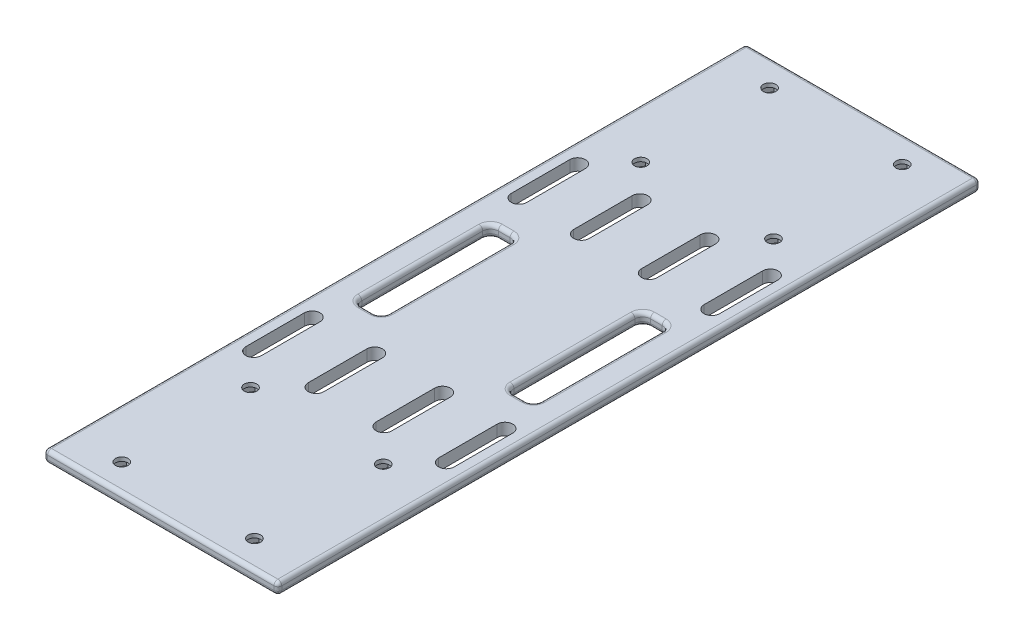
SolidWorks part; units mm, degrees
ref_plane "Front" through (0, 0, 0) normal (0, 0, 1) x (1, 0, 0)
ref_plane "Top" through (0, 0, 0) normal (0, 1, 0) x (1, 0, 0)
ref_plane "Right" through (0, 0, 0) normal (1, 0, 0) x (0, 0, -1)
sketch "Sketch1" plane through (0, 0, 0) normal (0, 1, 0) x (1, 0, 0)
  line L0 (0, 75.349) -> (0, -71.6607) construction
  line L1 (-30, 90) -> (30, 90)
  line L2 (-30, 90) -> (-30, -90)
  line L3 (-30, -90) -> (30, -90)
  line L4 (30, 90) -> (30, -90)
  line L5 (-30, 90) -> (30, -90) construction
  line L6 (-30, -90) -> (30, 90) construction
  line L7 (-47.0197, 0) -> (48.1207, 0) construction
  circle A0 centre (-17, 83) radius 1.6
  circle A1 centre (-17, 50) radius 1.6
  circle A2 centre (17, 50) radius 1.6
  circle A3 centre (17, 83) radius 1.6
  circle A4 centre (-17, -50) radius 1.6
  circle A5 centre (17, -50) radius 1.6
  circle A6 centre (17, -83) radius 1.6
  circle A7 centre (-17, -83) radius 1.6
  point P0 (0, 0)
  dimension "D3" = 3.2
  dimension "D1" = 60
  dimension "D2" = 180
  dimension "D4" = 7
  dimension "D5" = 13
  dimension "D6" = 33
extrude "Boss-Extrude1" add sketch "Sketch1" along normal blind 3
sketch "Sketch2" plane through (0, 3, 0) normal (0, 1, 0) x (1, 0, 0)
  line L8 (0, -69.3107) -> (0, 75.504) construction
  line L15 (30, -90) -> (30, 90) construction
  line L16 (21, -17.5) -> (18, -17.5)
  line L17 (23, -15.5) -> (23, 15.5)
  line L18 (21, 17.5) -> (18, 17.5)
  line L19 (16, -15.5) -> (16, 15.5)
  line L20 (23, -17.5) -> (16, 17.5) construction
  line L21 (23, 17.5) -> (16, -17.5) construction
  line L22 (-23, 17.5) -> (-16, -17.5) construction
  line L23 (-23, -17.5) -> (-16, 17.5) construction
  line L24 (-16, -15.5) -> (-16, 15.5)
  line L25 (-21, 17.5) -> (-18, 17.5)
  line L26 (-23, -15.5) -> (-23, 15.5)
  line L27 (-21, -17.5) -> (-18, -17.5)
  arc A0 (18, -17.5) -> (16, -15.5) centre (18, -15.5) cw
  arc A1 (21, -17.5) -> (23, -15.5) centre (21, -15.5) ccw
  arc A2 (18, 17.5) -> (16, 15.5) centre (18, 15.5) ccw
  arc A3 (23, 15.5) -> (21, 17.5) centre (21, 15.5) ccw
  arc A4 (-23, 15.5) -> (-21, 17.5) centre (-21, 15.5) cw
  arc A5 (-18, 17.5) -> (-16, 15.5) centre (-18, 15.5) cw
  arc A6 (-21, -17.5) -> (-23, -15.5) centre (-21, -15.5) cw
  arc A7 (-18, -17.5) -> (-16, -15.5) centre (-18, -15.5) ccw
  point P0 (19.5, 0)
  point P7 (16, 0)
  point P39 (-19.5, 0)
  dimension "D1" = 7
  dimension "D4" = 2
  dimension "D2" = 35
  dimension "D3" = 7
extrude "Cut-Extrude1" cut sketch "Sketch2" against normal blind 72
fillet "Fillet2" radius 1 2 edges at (-30, 3, 0) (30, 0, 0)
sketch "Sketch3" plane through (0, 0, 0) normal (0, -1, 0) x (-1, 0, 0)
  circle A0 centre (0, 30.4779) radius 1
extrude "Cut-Extrude2" cut sketch "Sketch3" against normal blind 1
sketch "Sketch4" plane through (0, 0, 0) normal (0, -1, 0) x (-1, 0, 0)
  line L1 (-13.8246, 83) -> (-15.4123, 85.75)
  line L2 (-15.4123, 85.75) -> (-18.5877, 85.75)
  line L3 (-18.5877, 85.75) -> (-20.1754, 83)
  line L4 (-20.1754, 83) -> (-18.5877, 80.25)
  line L5 (-18.5877, 80.25) -> (-15.4123, 80.25)
  line L6 (-15.4123, 80.25) -> (-13.8246, 83)
  line L7 (20.1754, 83) -> (18.5877, 85.75)
  line L8 (18.5877, 85.75) -> (15.4123, 85.75)
  line L9 (15.4123, 85.75) -> (13.8246, 83)
  line L10 (13.8246, 83) -> (15.4123, 80.25)
  line L11 (15.4123, 80.25) -> (18.5877, 80.25)
  line L12 (18.5877, 80.25) -> (20.1754, 83)
  line L13 (-13.8246, 50) -> (-15.4123, 52.75)
  line L14 (-15.4123, 52.75) -> (-18.5877, 52.75)
  line L15 (-18.5877, 52.75) -> (-20.1754, 50)
  line L16 (-20.1754, 50) -> (-18.5877, 47.25)
  line L17 (-18.5877, 47.25) -> (-15.4123, 47.25)
  line L18 (-15.4123, 47.25) -> (-13.8246, 50)
  line L19 (20.1754, 50) -> (18.5877, 52.75)
  line L20 (18.5877, 52.75) -> (15.4123, 52.75)
  line L21 (15.4123, 52.75) -> (13.8246, 50)
  line L22 (13.8246, 50) -> (15.4123, 47.25)
  line L23 (15.4123, 47.25) -> (18.5877, 47.25)
  line L24 (18.5877, 47.25) -> (20.1754, 50)
  circle A0 centre (-17, 83) radius 2.75 construction
  circle A1 centre (17, 83) radius 2.75 construction
  circle A2 centre (-17, 50) radius 2.75 construction
  circle A3 centre (17, 50) radius 2.75 construction
  circle M49 centre (17, 83) radius 1.6
  circle M50 centre (17, 50) radius 1.6
  circle M51 centre (-17, 50) radius 1.6
  circle M52 centre (-17, 83) radius 1.6
  dimension "D1" = 5.5
extrude "Cut-Extrude3" cut sketch "Sketch4" against normal blind 2 contours L11 L12 L7 L8 L9 L10 M49 | L23 L24 L19 L20 L21 L22 M50 | L17 L18 L13 L14 L15 L16 M51 | L5 L6 L1 L2 L3 L4 M52
mirror "Mirror1" about plane through (0, 0, 0) normal (0, 0, 1) of "Cut-Extrude3"
fillet "Fillet3" radius 1 14 edges at (30, 2, -90) (-0.5, 0, -90) (-0.5, 0, 90) (30, 2, 90) (-30, 1, -90) (-29.7071, 2.7071, -90) (29.7071, 0.2929, -90) (29.7071, 0.2929, 90) (0.5, 3, -90) (30, 3, 0) (-30, 0, 0) (-30, 1, 90) (-29.7071, 2.7071, 90) (0.5, 3, 90)
fillet "Fillet4" radius 1 32 edges at (-16.5858, 3, 16.9142) (-19.5, 3, 17.5) (-22.4142, 3, 16.9142) (-23, 3, 0) (-22.4142, 3, -16.9142) (-19.5, 3, -17.5) (-16.5858, 3, -16.9142) (22.4142, 3, 16.9142) (19.5, 3, 17.5) (16.5858, 3, 16.9142) (16, 3, 0) (16.5858, 3, -16.9142) (19.5, 3, -17.5) (22.4142, 3, -16.9142) (16.5858, 0, -16.9142) (19.5, 0, -17.5) (22.4142, 0, -16.9142) (23, 0, 0) (22.4142, 0, 16.9142) (19.5, 0, 17.5) (16.5858, 0, 16.9142) (-22.4142, 0, -16.9142) (-19.5, 0, -17.5) (-16.5858, 0, -16.9142) (-16.5858, 0, 16.9142) (-19.5, 0, 17.5) (-22.4142, 0, 16.9142) (-16, 3, 0) (-16, 0, 0) (23, 3, 0) (16, 0, 0) (-23, 0, 0)
sketch "Sketch5" plane through (0, 3, 0) normal (0, 1, 0) x (1, 0, 0)
  line L0 (-24.6978, -26.5) -> (-24.6978, -41.5) construction
  line L1 (-8.6978, -26.5) -> (-8.6978, -41.5) construction
  line L2 (-22.6978, -26.5) -> (-22.6978, -41.5)
  line L3 (-26.6978, -26.5) -> (-26.6978, -41.5)
  line L4 (-6.6978, -26.5) -> (-6.6978, -41.5)
  line L5 (-10.6978, -26.5) -> (-10.6978, -41.5)
  line L6 (-29, 89) -> (-29, -89) construction
  line L7 (-29, -89) -> (29, -89) construction
  line L8 (0, 0) -> (0, -141.9322) construction
  line L9 (24.6978, -26.5) -> (24.6978, -41.5) construction
  line L10 (22.6978, -26.5) -> (22.6978, -41.5)
  line L11 (26.6978, -26.5) -> (26.6978, -41.5)
  line L12 (8.6978, -26.5) -> (8.6978, -41.5) construction
  line L13 (6.6978, -26.5) -> (6.6978, -41.5)
  line L14 (10.6978, -26.5) -> (10.6978, -41.5)
  arc A0 (-22.6978, -26.5) -> (-26.6978, -26.5) centre (-24.6978, -26.5) ccw
  arc A1 (-26.6978, -41.5) -> (-22.6978, -41.5) centre (-24.6978, -41.5) ccw
  arc A2 (-6.6978, -26.5) -> (-10.6978, -26.5) centre (-8.6978, -26.5) ccw
  arc A3 (-10.6978, -41.5) -> (-6.6978, -41.5) centre (-8.6978, -41.5) ccw
  arc A4 (22.6978, -26.5) -> (26.6978, -26.5) centre (24.6978, -26.5) cw
  arc A5 (26.6978, -41.5) -> (22.6978, -41.5) centre (24.6978, -41.5) cw
  arc A6 (6.6978, -26.5) -> (10.6978, -26.5) centre (8.6978, -26.5) cw
  arc A7 (10.6978, -41.5) -> (6.6978, -41.5) centre (8.6978, -41.5) cw
  point P4 (-24.6978, -34)
  point P9 (-8.6978, -34)
  point P23 (24.6978, -34)
  point P30 (8.6978, -34)
  dimension "D1" = 2
  dimension "D2" = 4.3022
  dimension "D3" = 55
  dimension "D4" = 16
  dimension "D5" = 15
  dimension "D6" = 15
extrude "Cut-Extrude4" cut sketch "Sketch5" against normal blind 10
mirror "Mirror2" about plane through (0, 0, 0) normal (0, 0, 1) of "Cut-Extrude4"
